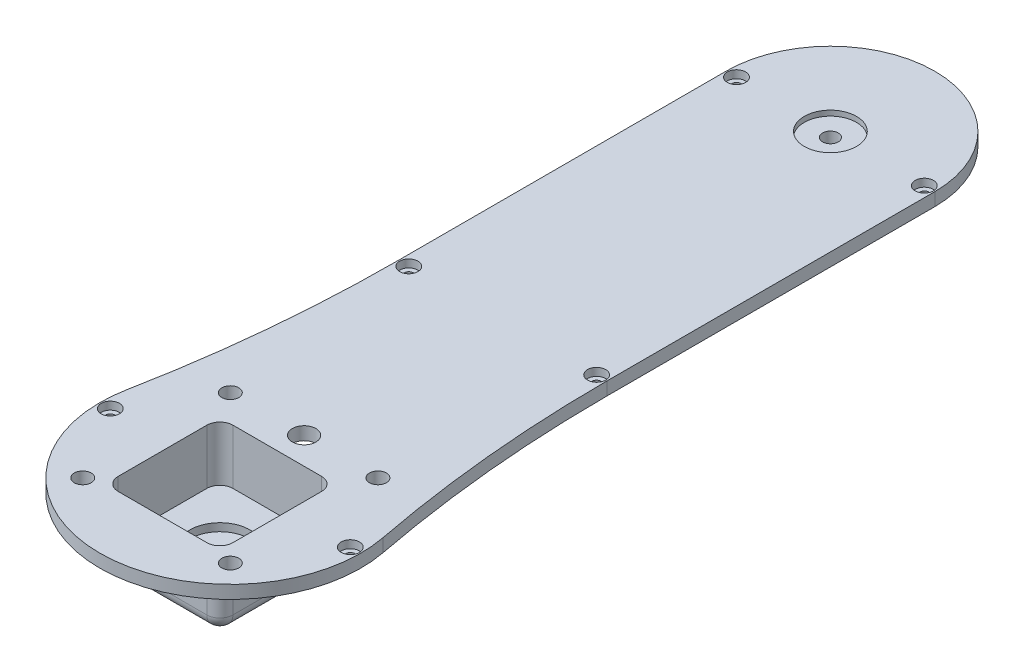
SolidWorks part; units mm, degrees
ref_plane "前视基准面" through (0, 0, 0) normal (0, 0, 1) x (1, 0, 0)
ref_plane "上视基准面" through (0, 0, 0) normal (0, 1, 0) x (1, 0, 0)
ref_plane "右视基准面" through (0, 0, 0) normal (1, 0, 0) x (0, 0, -1)
other "Configuration Table"
sketch "草图1" plane through (0, 0, 0) normal (0, 1, 0) x (1, 0, 0)
  line L2 (-40, 104.4031) -> (-40, 230)
  line L4 (40, 230) -> (40, 104.4031)
  arc A0 (-49.0909, 9.4912) -> (49.0909, 9.4912) centre (0, 0) ccw
  arc A2 (49.0909, 9.4912) -> (40, 104.4031) centre (540, 104.4031) cw
  arc A3 (-40, 104.4031) -> (-49.0909, 9.4912) centre (-540, 104.4031) cw
  arc A4 (40, 230) -> (-40, 230) centre (0, 230) ccw construction
  arc A5 (40, 230) -> (-40, 230) centre (0, 230) ccw
  dimension "D1" = 100
  dimension "D2" = 500
extrude "凸台-拉伸1" add sketch "草图1" along normal blind 5
sketch "草图2" plane through (0, 5, 0) normal (0, 1, 0) x (1, 0, 0)
  circle A0 centre (28.2843, 28.2843) radius 3.25
  circle A1 centre (28.2843, -28.2843) radius 3.25
  circle A2 centre (-28.2843, -28.2843) radius 3.25
  circle A3 centre (-28.2843, 28.2843) radius 3.25
  point P12 (0, 0)
  dimension "D1" = 6.5
  dimension "D2" = 4
extrude "切除-拉伸1" cut sketch "草图2" against normal blind 5
sketch "草图10" plane through (0, 0, 0) normal (0, -1, 0) x (1, 0, 0)
  line L0 (0, 0) -> (0, -50000) construction
  circle A0 centre (46, 0) radius 1.75
  circle A1 centre (36, -104.4031) radius 1.75
  circle A2 centre (36, -230) radius 1.75
  circle A3 centre (-36, -230) radius 1.75
  circle A4 centre (-36, -104.4031) radius 1.75
  circle A5 centre (-46, 0) radius 1.75
  dimension "D1" = 3.5
  dimension "D2" = 3.5
  dimension "D3" = 3.5
extrude "切除-拉伸8" cut sketch "草图10" against normal blind 45
sketch "草图11" plane through (0, 5, 0) normal (0, 1, 0) x (1, 0, 0)
  line L0 (0, 270) -> (0, -49730) construction
  circle A0 centre (-36, 230) radius 3.5
  circle A1 centre (-36, 104.4031) radius 3.5
  circle A2 centre (-46, 0) radius 3.5
  arc A3 (40, 230) -> (-40, 230) centre (0, 230) ccw construction
  circle A4 centre (46, 0) radius 3.5
  circle A5 centre (36, 104.4031) radius 3.5
  circle A6 centre (36, 230) radius 3.5
  point P14 (0, 270)
  dimension "D1" = 7
  dimension "D2" = 7
  dimension "D3" = 7
extrude "切除-拉伸9" cut sketch "草图11" against normal blind 3
sketch "草图12" plane through (0, 5, 0) normal (0, 1, 0) x (1, 0, 0)
  line L0 (0, 0) -> (0, 50000) construction
  line L1 (-22, -26) -> (22, -26)
  line L2 (-22, -26) -> (-22, 18)
  line L3 (-22, 18) -> (22, 18)
  line L4 (22, -26) -> (22, 18)
  line L5 (-22, -26) -> (22, 18) construction
  line L6 (-22, 18) -> (22, -26) construction
  point P0 (0, -4)
  point P5 (0, 3.8158)
  point P9 (0, -1.668)
  point P11 (0, 2.4013)
  dimension "D1" = 44
  dimension "D2" = 44
  dimension "D3" = 26
  dimension "D4" = 4
extrude "切除-拉伸10" cut sketch "草图12" against normal blind 5
sketch "草图13" plane through (0, 0, 0) normal (0, -1, 0) x (1, 0, 0)
  line L1 (-22, 26) -> (22, 26)
  line L2 (-22, 26) -> (-22, -18)
  line L3 (-22, -18) -> (22, -18)
  line L4 (22, 26) -> (22, -18)
  line L5 (-21, 30) -> (21, 30)
  line L6 (-26, 25) -> (-26, -17)
  line L7 (-21, -22) -> (21, -22)
  line L8 (26, 25) -> (26, -17)
  arc A0 (21, -22) -> (26, -17) centre (21, -17) ccw
  arc A1 (21, 30) -> (26, 25) centre (21, 25) cw
  arc A2 (-26, -17) -> (-21, -22) centre (-21, -17) ccw
  arc A3 (-21, 30) -> (-26, 25) centre (-21, 25) ccw
  dimension "D5" = 5
  dimension "D1" = 4
  dimension "D2" = 4
  dimension "D3" = 4
  dimension "D4" = 4
extrude "凸台-拉伸2" add sketch "草图13" along normal blind 16
ref_plane "基准面1" through (22, -16, 26) normal (-1, 0, 0) x (0, 0, 1)
sketch "草图15" plane through (0, -16, 0) normal (0, -1, 0) x (1, 0, 0)
  line L24 (26, -17) -> (26, 25)
  line L25 (-21, -22) -> (21, -22)
  line L26 (-26, 25) -> (-26, -17)
  line L27 (21, 30) -> (-21, 30)
  line L28 (26, -17) -> (26, 25)
  line L29 (-21, -22) -> (21, -22)
  line L30 (-26, 25) -> (-26, -17)
  line L31 (21, 30) -> (-21, 30)
  arc A20 (26, 25) -> (21, 30) centre (21, 25) ccw
  arc A21 (21, -22) -> (26, -17) centre (21, -17) ccw
  arc A22 (-26, -17) -> (-21, -22) centre (-21, -17) ccw
  arc A23 (-21, 30) -> (-26, 25) centre (-21, 25) ccw
  arc A24 (26, 25) -> (21, 30) centre (21, 25) ccw
  arc A25 (21, -22) -> (26, -17) centre (21, -17) ccw
  arc A26 (-26, -17) -> (-21, -22) centre (-21, -17) ccw
  arc A27 (-21, 30) -> (-26, 25) centre (-21, 25) ccw
  dimension "D1" = 0
extrude "凸台-拉伸3" add sketch "草图15" along normal blind 4
fillet "圆角1" radius 5 8 edges at (26, -20, 4) (24.5355, -20, -20.5355) (0, -20, -22) (-24.5355, -20, -20.5355) (-26, -20, 4) (-24.5355, -20, 28.5355) (0, -20, 30) (24.5355, -20, 28.5355)
sketch "草图16" plane through (0, -16, 0) normal (0, 1, 0) x (1, 0, 0)
  line L0 (-22, -4) -> (49978, -4) construction
  line L1 (-22, 18) -> (-22, -26) construction
  line L2 (22, -26) -> (22, 18) construction
  circle A0 centre (0, -4) radius 11.5
  point P9 (-22, -4)
  point P12 (22, -4)
  dimension "D1" = 23
extrude "切除-拉伸11" cut sketch "草图16" against normal blind 3
sketch "草图17" plane through (0, -19, 0) normal (0, 1, 0) x (1, 0, 0)
  circle A0 centre (0, -4) radius 3
  dimension "D1" = 6
extrude "切除-拉伸12" cut sketch "草图17" against normal blind 3
fillet "圆角2" radius 5 4 edges at (22, -5.5, 26) (-22, -5.5, 26) (-22, -5.5, -18) (22, -5.5, -18)
sketch "草图20" plane through (0, 0, 0) normal (0, -1, 0) x (1, 0, 0)
  circle A0 centre (0, -230) radius 3
  dimension "D1" = 6
extrude "切除-拉伸14" cut sketch "草图20" against normal blind 39
sketch "草图21" plane through (0, 0, 0) normal (0, -1, 0) x (1, 0, 0)
  circle A0 centre (0, -230) radius 4.5
  circle A1 centre (0, -230) radius 3
  dimension "D1" = 9
extrude "凸台-拉伸4" add sketch "草图21" along normal blind 20
chamfer "倒角1" distance 10 angle 60 1 edges at (0, 0, -234.5)
sketch "草图22" plane through (0, 5, 0) normal (0, 1, 0) x (1, 0, 0)
  circle A0 centre (0, 230) radius 10
  dimension "D1" = 20
extrude "切除-拉伸15" cut sketch "草图22" against normal blind 2
sketch "草图23" plane through (0, 5, 0) normal (0, 1, 0) x (1, 0, 0)
  circle A0 centre (0, 28.2843) radius 4.5
  dimension "D1" = 9
extrude "切除-拉伸16" cut sketch "草图23" against normal blind 5
